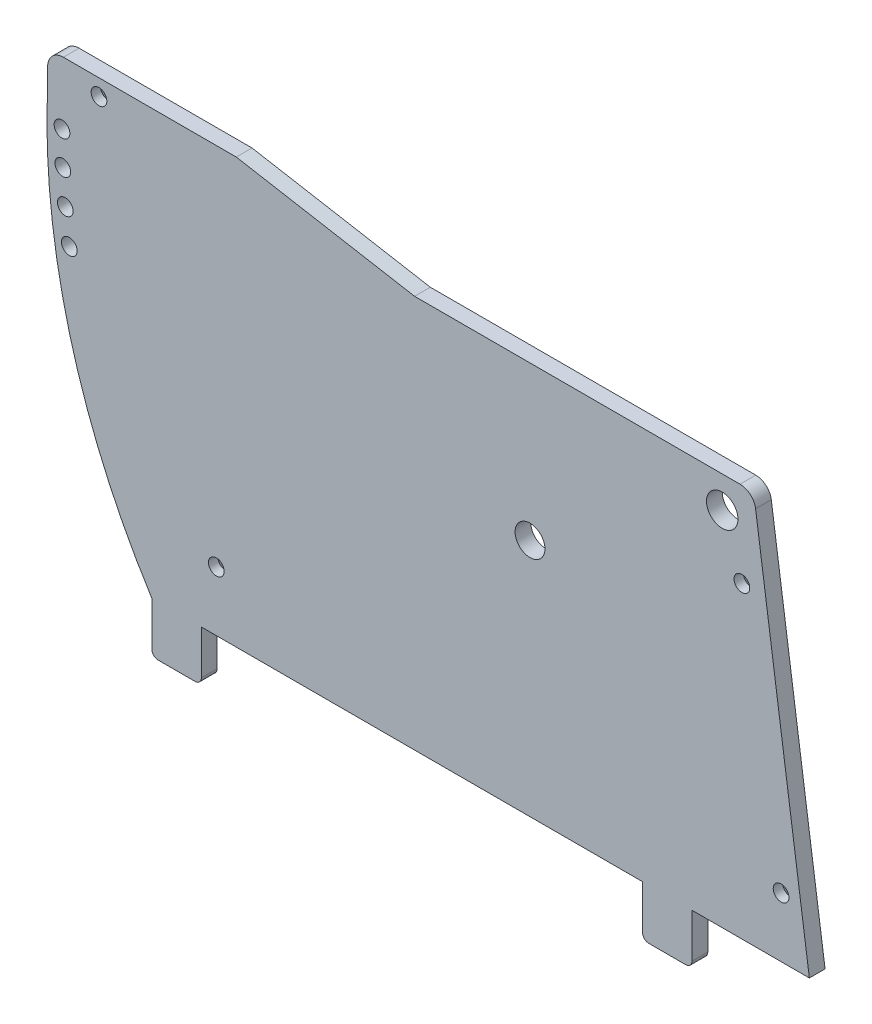
SolidWorks part; units mm, degrees
ref_plane "Front Plane" through (0, 0, 0) normal (0, 0, 1) x (1, 0, 0)
ref_plane "Top Plane" through (0, 0, 0) normal (0, 1, 0) x (1, 0, 0)
ref_plane "Right Plane" through (0, 0, 0) normal (1, 0, 0) x (0, 0, -1)
sketch "Sketch18" plane through (0, 0, 0) normal (0, 0, 1) x (1, 0, 0)
  line L0 (0, 0) -> (-265.6047, 0)
  line L4 (0, 0) -> (-21.7272, 153.2911)
  line L5 (-28.0144, 158.75) -> (-159.4738, 158.75)
  line L6 (-159.4738, 158.75) -> (-231.4991, 171.45)
  line L7 (-231.4991, 171.45) -> (-301.3491, 171.45)
  line L8 (-307.6991, 165.1) -> (-307.6991, 158.75)
  circle A0 centre (-180.594, 136.144) radius 1.905
  arc A1 (-307.6991, 158.75) -> (-265.6047, 0) centre (-35.2009, 146.05) ccw
  arc A2 (-21.7272, 153.2911) -> (-28.0144, 158.75) centre (-28.0144, 152.4) ccw
  arc A3 (-301.3491, 171.45) -> (-307.6991, 165.1) centre (-301.3491, 165.1) ccw
  circle A4 centre (-11.4235, 24.0347) radius 3.175
  circle A5 centre (-27.2534, 124.4065) radius 3.175
  circle A6 centre (-35.2009, 146.05) radius 6.35
  circle A7 centre (-301.9009, 146.05) radius 3.175
  circle A8 centre (-301.5697, 132.7614) radius 3.175
  circle A9 centre (-300.5799, 119.5375) radius 3.175
  circle A10 centre (-298.9435, 106.4428) radius 3.175
  circle A11 centre (-239.5689, 24.0347) radius 3.175
  circle A12 centre (-286.9621, 164.8507) radius 3.175
  circle A13 centre (-187.097, 107.95) radius 2.5
  circle A14 centre (-180.594, 105.156) radius 1.905
  circle A15 centre (-165.1, 120.65) radius 10.922
  circle A16 centre (-165.1, 146.05) radius 2.5
  circle A17 centre (-149.606, 105.156) radius 1.905
  circle A18 centre (-149.606, 136.144) radius 1.905
  circle A19 centre (-143.103, 107.95) radius 2.5
  circle A20 centre (-35.2009, 146.05) radius 266.7 construction
  dimension "D7" = 13.2886
  dimension "D8" = 13.2239
  dimension "D9" = 13.0947
  dimension "D11" = 6.35
  dimension "D12" = 20.7369
  dimension "D16" = 6.35
  dimension "D17" = 6.35
  dimension "D19" = 43.9941
  dimension "D20" = 21.997
  dimension "D21" = 15.494
  dimension "D22" = 15.494
  dimension "D23" = 30.988
  dimension "D24" = 30.988
  dimension "D25" = 30.988
  dimension "D26" = 15.494
  dimension "D2" = 158.75
  dimension "D3" = 81.933
  dimension "D4" = 12.7
  dimension "D6" = 25.4
  dimension "D13" = 6.5993
  dimension "D14" = 76.2
  dimension "D15" = 72.0253
extrude "Boss-Extrude4" add sketch "Sketch18" along normal blind 6.35 separate body
chamfer "Chamfer1" distance 2.54 angle 45 4 edges at (-24.0784, 124.4065, 0) (-8.2485, 24.0347, 0) (-236.3939, 24.0347, 0) (-283.7871, 164.8507, 0)
sketch "Sketch19" plane through (0, 0, 0) normal (0, 0, -1) x (-1, 0, 0)
  circle A0 centre (165.1, 120.65) radius 32.8088
extrude "Boss-Extrude5" add sketch "Sketch19" against normal up to surface (6.35 mm away) up to face at (-147.701, 136.144, 6.35)
sketch "Sketch20" plane through (0, 0, 0) normal (0, 0, -1) x (-1, 0, 0)
  circle A0 centre (112.8435, 96.6743) radius 6.0325 construction
  circle A1 centre (112.8435, 96.6743) radius 6.0325
extrude "Cut-Extrude1" cut sketch "Sketch20" against normal up to surface (6.35 mm away) up to face at (-283.7871, 164.8507, 6.35)
sketch "Sketch22" plane through (0, 0, 0) normal (0, -1, 0) x (1, 0, 0)
  line L0 (-265.6047, 0) -> (0, 0) construction
  line L1 (-47.3848, 0) -> (-67.3848, 0)
  line L2 (-47.3848, 0) -> (-47.3848, 6.35)
  line L3 (-47.3848, 6.35) -> (-67.3848, 6.35)
  line L4 (-67.3848, 0) -> (-67.3848, 6.35)
  line L5 (-47.3848, 6.35) -> (-47.3848, 0) construction
  line L6 (-265.6047, 6.35) -> (0, 6.35) construction
  line L7 (-67.3848, 0) -> (-67.3848, 6.35) construction
  line L8 (-245.6047, 6.35) -> (-245.6047, 0) construction
  line L9 (-245.6047, 6.35) -> (-265.6047, 6.35)
  line L10 (-245.6047, 6.35) -> (-245.6047, 0)
  line L11 (-245.6047, 0) -> (-265.6047, 0)
  line L12 (-265.6047, 6.35) -> (-265.6047, 0)
extrude "Boss-Extrude6" add sketch "Sketch22" along normal up to surface (20.32 mm away)
fillet "Fillet1" radius 2.54 4 edges at (-265.6047, -20.32, 3.175) (-245.6047, -20.32, 3.175) (-67.3848, -20.32, 3.175) (-47.3848, -20.32, 3.175)
